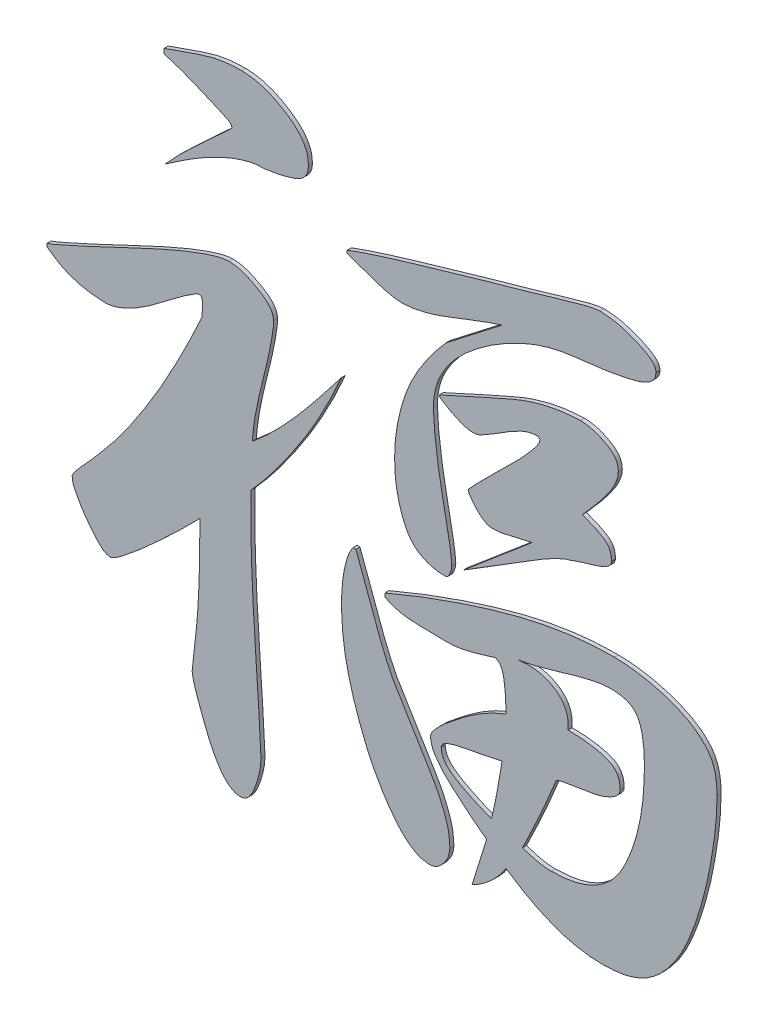
SolidWorks part; units mm, degrees
ref_plane "前视基准面" through (0, 0, 0) normal (0, 0, 1) x (1, 0, 0)
ref_plane "上视基准面" through (0, 0, 0) normal (0, 1, 0) x (1, 0, 0)
ref_plane "右视基准面" through (0, 0, 0) normal (1, 0, 0) x (0, 0, -1)
other "Configuration Table"
sketch "草图1" plane through (0, 0, 0) normal (0, 0, 1) x (1, 0, 0)
  text T0 "福" font "祥南行書体" height 25
extrude "凸台-拉伸1" add sketch "草图1" along normal blind 0.2
